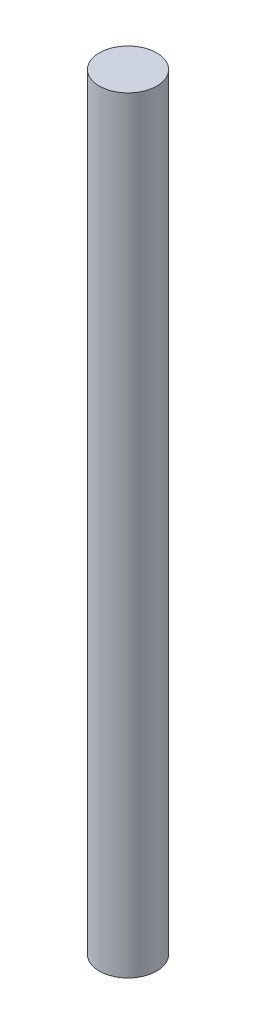
SolidWorks part; units mm, degrees
ref_plane "前视基准面" through (0, 0, 0) normal (0, 0, 1) x (1, 0, 0)
ref_plane "上视基准面" through (0, 0, 0) normal (0, 1, 0) x (1, 0, 0)
ref_plane "右视基准面" through (0, 0, 0) normal (1, 0, 0) x (0, 0, -1)
ref_plane "基准面4" through (0, 0, 36.9421) normal (0, 0, 1) x (1, 0, 0)
sketch "草图1" plane through (0, 0, 36.9421) normal (0, 0, 1) x (1, 0, 0)
  line L0 (-31.6293, 40) -> (-33.1293, 40)
  line L1 (-33.1293, 40) -> (-33.1293, 0)
  line L2 (-33.1293, 0) -> (-31.6293, 0)
  line L3 (-31.6293, 0) -> (-31.6293, 40)
  line L4 (-33.1293, 40) -> (-33.1293, 0) construction
revolve "旋转1" add sketch "草图1" angle 360 about L4
